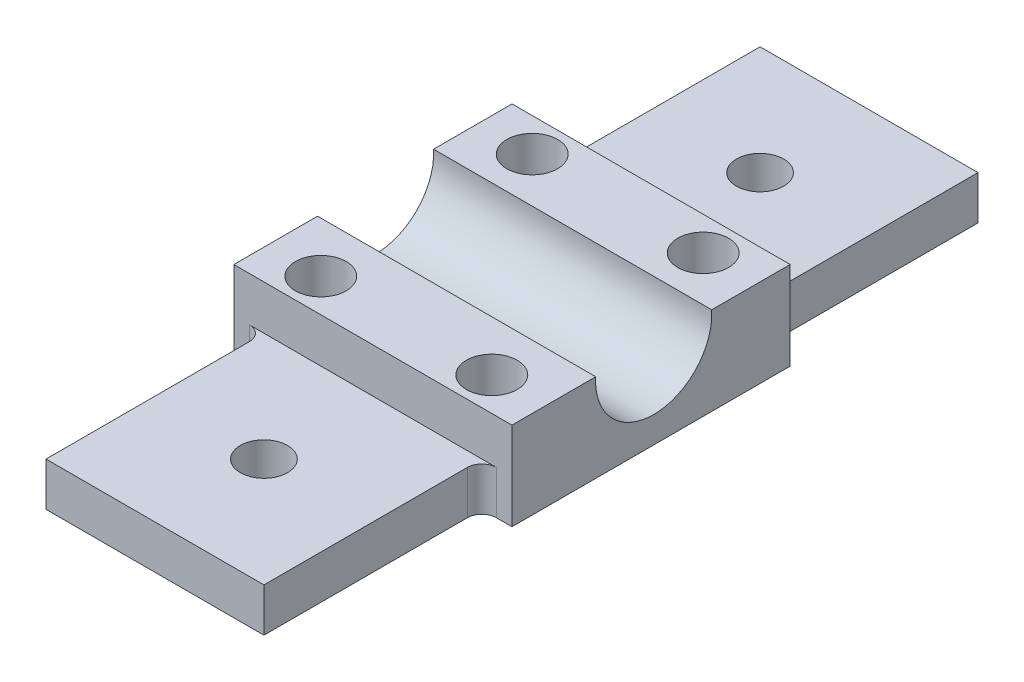
SolidWorks part; units mm, degrees
ref_plane "Front Plane" through (0, 0, 0) normal (0, 0, 1) x (1, 0, 0)
ref_plane "Top Plane" through (0, 0, 0) normal (0, 1, 0) x (1, 0, 0)
ref_plane "Right Plane" through (0, 0, 0) normal (1, 0, 0) x (0, 0, -1)
sketch "Sketch1" plane through (0, 0, 0) normal (0, 1, 0) x (1, 0, 0)
  line L6 (-19.145, 19.15) -> (19.145, 19.15)
  line L7 (-19.145, 19.15) -> (-19.145, -19.15)
  line L8 (-19.145, -19.15) -> (19.145, -19.15)
  line L9 (19.145, 19.15) -> (19.145, -19.15)
  line L10 (-19.145, 19.15) -> (19.145, -19.15) construction
  line L11 (-19.145, -19.15) -> (19.145, 19.15) construction
  point P11 (0, 0)
  dimension "D4" = 38.29
  dimension "D5" = 38.3
extrude "Boss-Extrude1" add sketch "Sketch1" along normal blind 12.12
sketch "Sketch2" plane through (19.145, 0, 0) normal (1, 0, 0) x (0, 0, -1)
  line L0 (-9.2164, 12.12) -> (-7.5, 7.11)
  line L1 (-19.15, 12.12) -> (19.15, 12.12) construction
  line L2 (-7.5, 7.11) -> (7.5, 7.11)
  line L3 (0, 7.11) -> (0, 0) construction
  line L4 (-9.2164, 12.12) -> (9.2164, 12.12)
  line L5 (9.2164, 12.12) -> (7.5, 7.11)
  line L6 (-19.15, 0) -> (19.15, 0) construction
  line L7 (-5.4456, 17.12) -> (6.1733, 17.12)
  line L8 (-7.6205, 12.12) -> (8.3482, 12.12)
  circle A0 centre (0.3638, 11.62) radius 8
  dimension "D2" = 16
  dimension "D1" = 7.11
  dimension "D3" = 15
  dimension "D5" = 2.5
  dimension "D6" = 5
extrude "Cut-Extrude1" cut sketch "Sketch2" against normal through all contours L4 A0 L2 | L3 L2 A0 | L2 L3 A0
hole_wizard "M8x1.0 Tapped Hole2" positions "Sketch6" profile "Sketch7" tap size "M8x1.0" standard "ANSI Metric" end condition through all
sketch "Sketch6" plane through (0, 12.12, 0) normal (0, 1, 0) x (1, 0, 0)
  line L0 (0, 0) -> (-19.145, 0) construction
  line L4 (0, 0) -> (0, 19.15) construction
  line L5 (19.145, 19.15) -> (-19.145, 19.15) construction
  line L8 (-19.145, 19.15) -> (-19.145, -19.15) construction
  circle A1 centre (-11.77, 14.55) radius 4.125
  circle A2 centre (11.77, 14.55) radius 4.125
  circle A3 centre (11.77, -14.55) radius 4.125
  circle A4 centre (-11.77, -14.55) radius 4.125
  point P0 (-11.77, 14.55)
  point P18 (11.77, 14.55)
  point P25 (-11.77, -14.55)
  point P26 (11.77, -14.55)
  dimension "D1" = 8.25
  dimension "D2" = 15.29
  dimension "D3" = 20.85
sketch "Sketch7" plane through (-11.77, 12.12, -14.55) normal (1, 0, 0) x (0, 0, 1)
  line L0 (0, 0) -> (0, 12.12)
  line L1 (0, 12.12) -> (3.5, 12.12)
  line L2 (3.5, 12.12) -> (3.5, 0)
  line L5 (3.5, 0) -> (0, 0)
  line L11 (0, -6.35) -> (0, 107.95) construction
  dimension "Thru Tap Drill Dia." = 7
  dimension "Thru Tap Drill Depth" = 12.12
cosmetic thread "Hole Thread5" parameters "D2"=8
cosmetic thread "Hole Thread9" parameters "D2"=8
cosmetic thread "Hole Thread10" parameters "D2"=8
cosmetic thread "Hole Thread11" parameters "D2"=8
mirror "Mirror1" about plane through (0, 0, 0) normal (0, 0, 1) of "M8x1.0 Tapped Hole2" second plane through (0, 0, 0) second plane normal (1, 0, 0)
cosmetic thread "Hole Thread6" parameters "D2"=8
cosmetic thread "Hole Thread7" parameters "D2"=8
cosmetic thread "Hole Thread8" parameters "D2"=8
sketch "Sketch9" plane through (0, 0, 0) normal (0, -1, 0) x (1, 0, 0)
  line L0 (19.145, -19.15) -> (-19.145, -19.15) construction
  line L1 (15, -19.15) -> (-15, -19.15)
  line L2 (15, -19.15) -> (15, -49.15)
  line L3 (15, -49.15) -> (-15, -49.15)
  line L4 (-15, -19.15) -> (-15, -49.15)
  circle A0 centre (0, -34.15) radius 3.25
  point P6 (0, -19.15)
  point P7 (0, -19.15)
  dimension "D3" = 6.5
  dimension "D1" = 30
  dimension "D2" = 30
  dimension "D4" = 15
  dimension "D5" = 15
extrude "Boss-Extrude2" add sketch "Sketch9" against normal blind 6
mirror "Mirror2" about plane through (0, 0, 0) normal (0, 0, 1) of "Boss-Extrude2"
fillet "Fillet1" radius 2 4 edges at (15, 3, 19.15) (15, 3, -19.15) (-15, 3, 19.15) (-15, 3, -19.15)
